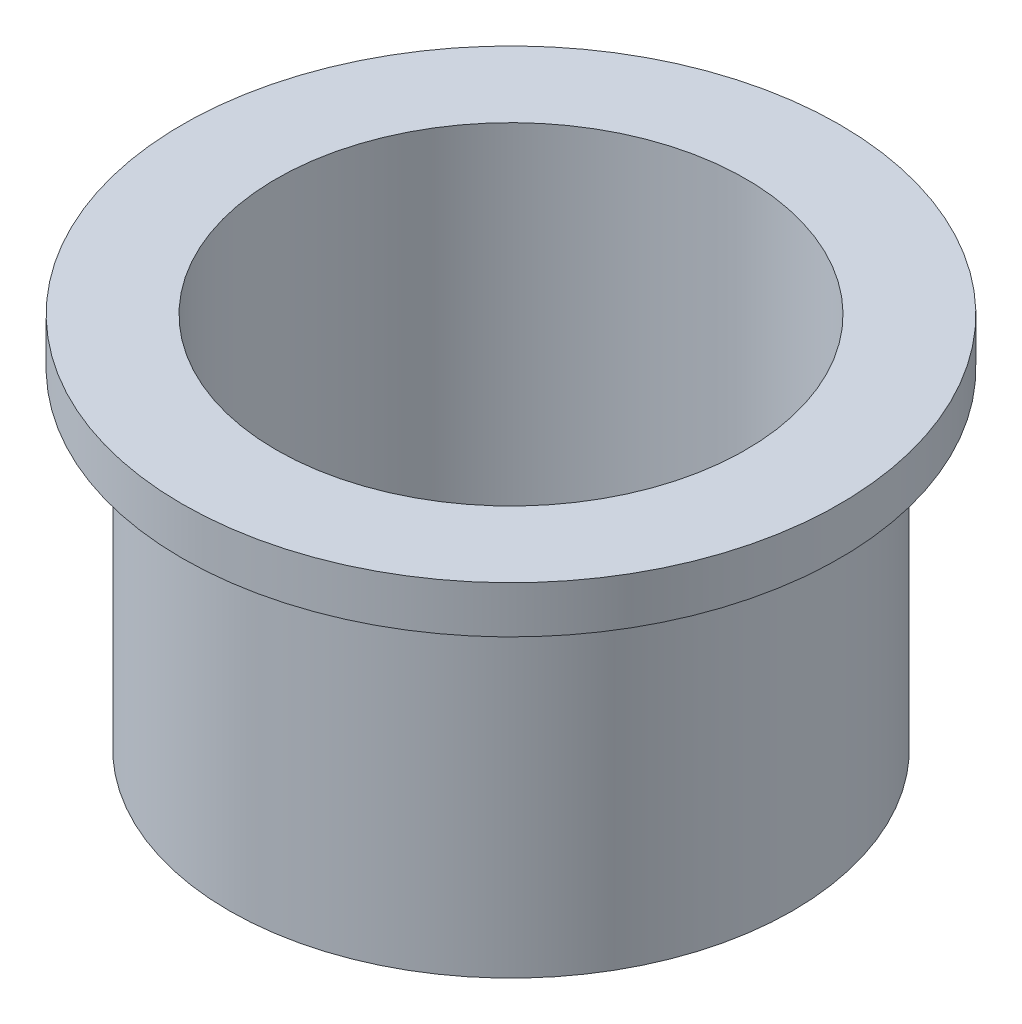
SolidWorks part; units mm, degrees
ref_plane "Front Plane" through (0, 0, 0) normal (0, 0, 1) x (1, 0, 0)
ref_plane "Top Plane" through (0, 0, 0) normal (0, 1, 0) x (1, 0, 0)
ref_plane "Right Plane" through (0, 0, 0) normal (1, 0, 0) x (0, 0, -1)
sketch "Sketch1" plane through (0, 0, 0) normal (0, 1, 0) x (1, 0, 0)
  circle A0 centre (0, 0) radius 15
  circle A1 centre (0, 0) radius 12.5
  dimension "D1" = 25
  dimension "D2" = 30
extrude "Boss-Extrude1" add sketch "Sketch1" along normal blind 20
sketch "Sketch2" plane through (0, 20, 0) normal (0, 1, 0) x (1, 0, 0)
  circle A0 centre (0, 0) radius 17.5
  circle A1 centre (0, 0) radius 15
  circle A2 centre (0, 0) radius 15 construction
  dimension "D1" = 35
extrude "Boss-Extrude2" add sketch "Sketch2" against normal blind 2.5
equation "\"inner_diameter\"=25.00"
equation "\"outer_diameter\"=30.00"
equation "\"length\"=20.00"
equation "\"flange_thickness\"=2.50"
equation "\"flange_diameter\"=35.00"
equation "\"D1@Sketch1\"=\"inner_diameter\""
equation "\"D2@Sketch1\"=\"outer_diameter\""
equation "\"D1@Boss-Extrude1\"=\"length\""
equation "\"D1@Sketch2\"=\"flange_diameter\""
equation "\"D1@Boss-Extrude2\"=\"flange_thickness\""
